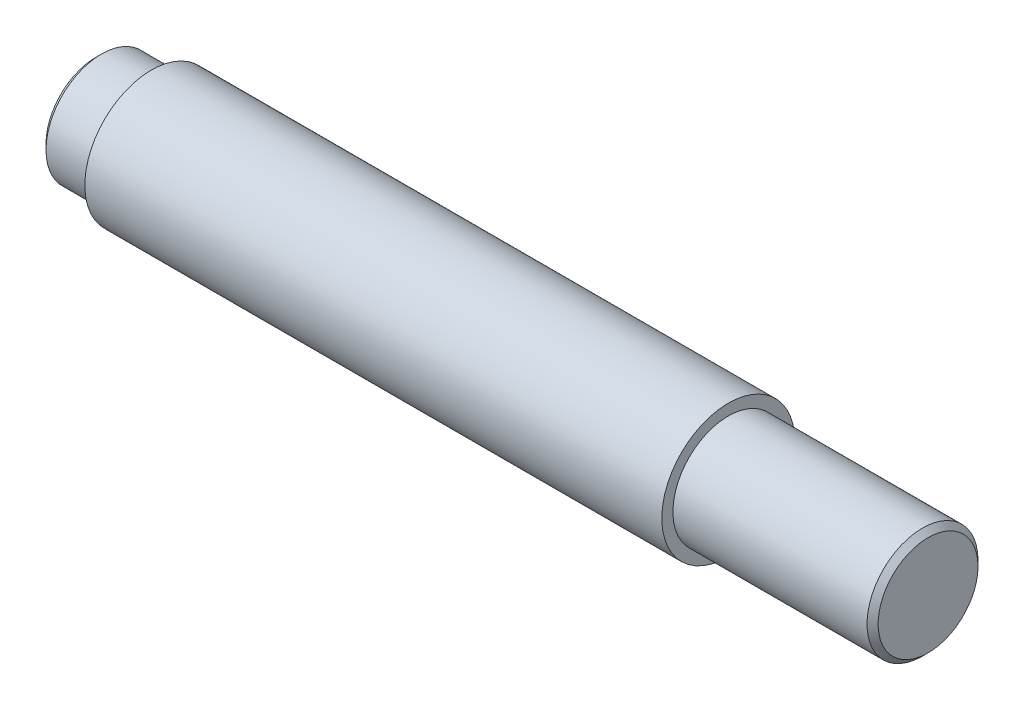
SolidWorks part; units mm, degrees
ref_plane "Front" through (0, 0, 0) normal (0, 0, 1) x (1, 0, 0)
ref_plane "Top" through (0, 0, 0) normal (0, 1, 0) x (1, 0, 0)
ref_plane "Right" through (0, 0, 0) normal (1, 0, 0) x (0, 0, -1)
sketch "草图1" plane through (0, 0, 0) normal (0, 1, 0) x (1, 0, 0)
  line L0 (-8.6304, 0) -> (-8.6304, 5)
  line L1 (-8.6304, 5) -> (-3.6304, 5)
  line L2 (-3.6304, 5) -> (-3.6304, 6)
  line L3 (-3.6304, 6) -> (48.3696, 6)
  line L4 (48.3696, 6) -> (48.3696, 5)
  line L5 (48.3696, 5) -> (66.3696, 5)
  line L6 (66.3696, 5) -> (66.3696, 0)
  line L7 (66.3696, 0) -> (-8.6304, 0)
  dimension "D1" = 5
  dimension "D2" = 5
  dimension "D3" = 75
  dimension "D4" = 18
  dimension "D5" = 5
  dimension "D6" = 6
revolve "旋转1" add sketch "草图1" angle 360 about L7
cosmetic thread "装饰螺纹线1" parameters "D2"=11
chamfer "倒角1" distance 0.5 angle 45 2 edges at (-8.6304, 0, -5) (66.3696, 0, -5)
